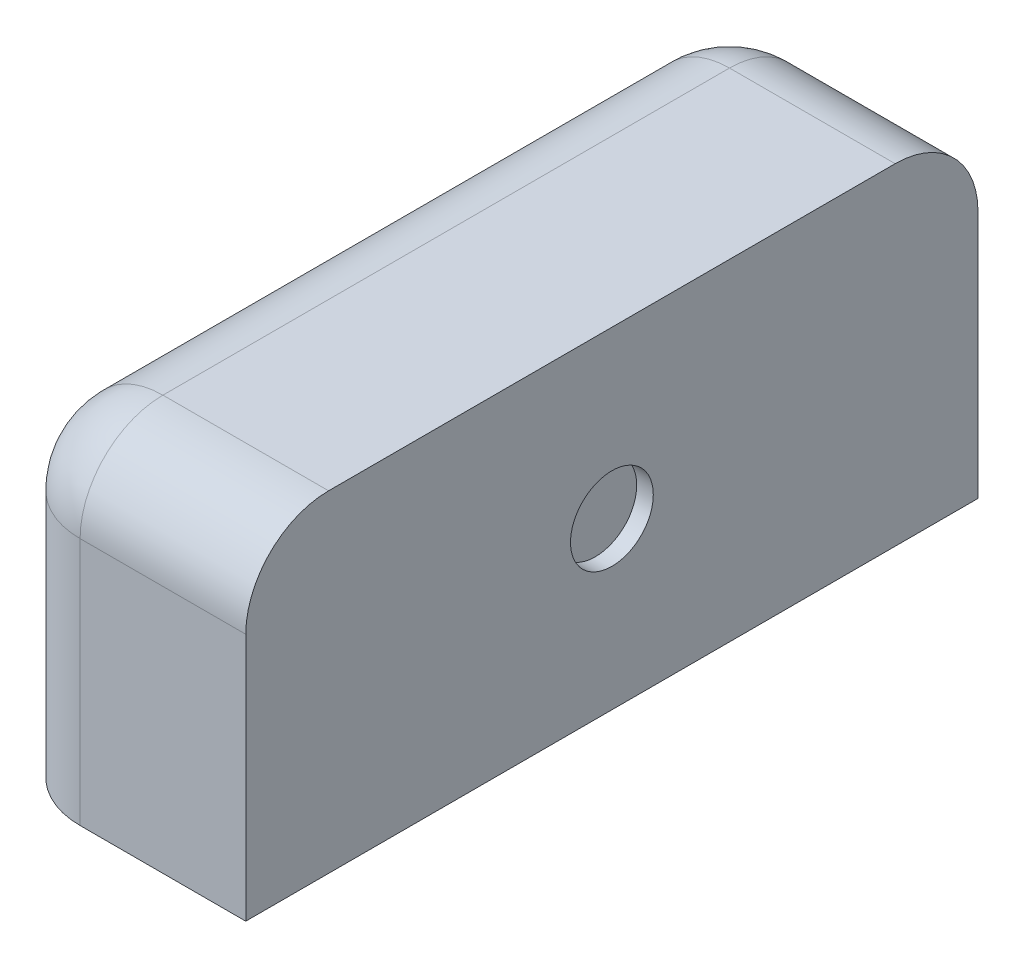
SolidWorks part; units mm, degrees
ref_plane "Front Plane" through (0, 0, 0) normal (0, 0, 1) x (1, 0, 0)
ref_plane "Top Plane" through (0, 0, 0) normal (0, 1, 0) x (1, 0, 0)
ref_plane "Right Plane" through (0, 0, 0) normal (1, 0, 0) x (0, 0, -1)
sketch "Sketch1" plane through (0, 0, 0) normal (0, 1, 0) x (1, 0, 0)
  line L1 (0, 0) -> (30, 0)
  line L2 (0, 0) -> (0, 88.4)
  line L3 (0, 88.4) -> (30, 88.4)
  line L4 (30, 0) -> (30, 88.4)
  dimension "D1" = 88.4
  dimension "D2" = 30
extrude "Boss-Extrude1" add sketch "Sketch1" along normal blind 40
fillet "Fillet1" radius 10 5 edges at (15, 40, -88.4) (15, 40, 0) (0, 40, -44.2) (0, 20, -88.4) (0, 20, 0)
sketch "Sketch2" plane through (30, 0, 0) normal (1, 0, 0) x (0, 0, -1)
  line L0 (0, 0) -> (88.4, 0) construction
  circle A0 centre (44.2, 20) radius 5
  point P4 (44.2, 0)
  dimension "D2" = 0
  dimension "D3" = 20
extrude "Cut-Extrude1" cut sketch "Sketch2" against normal blind 2
